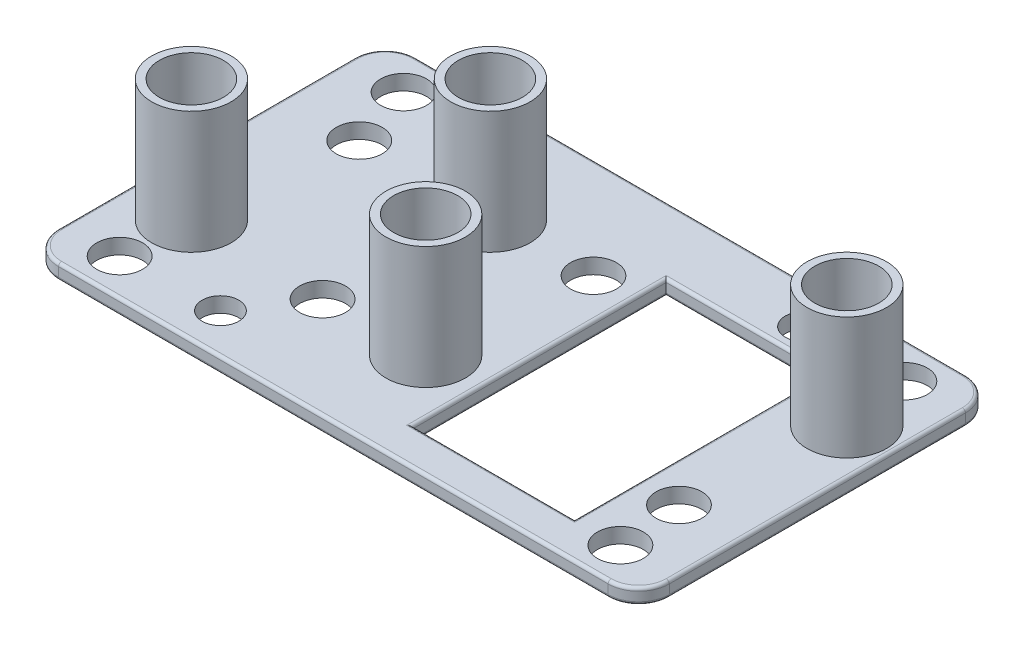
SolidWorks part; units mm, degrees
ref_plane "Front Plane" through (0, 0, 0) normal (0, 0, 1) x (1, 0, 0)
ref_plane "Top Plane" through (0, 0, 0) normal (0, 1, 0) x (1, 0, 0)
ref_plane "Right Plane" through (0, 0, 0) normal (1, 0, 0) x (0, 0, -1)
sketch "Sketch1" plane through (0, 0, 0) normal (0, 1, 0) x (1, 0, 0)
  line L1 (0, 0) -> (200, 0)
  line L2 (0, 0) -> (0, 117)
  line L3 (0, 117) -> (200, 117)
  line L4 (200, 0) -> (200, 117)
  line L5 (6.4676, 96) -> (81.4676, 96)
  line L6 (6.4676, 96) -> (6.4676, 21)
  line L7 (6.4676, 21) -> (81.4676, 21)
  line L8 (81.4676, 96) -> (81.4676, 21)
  line L9 (83.1891, 96) -> (198.1891, 96)
  line L10 (83.1891, 96) -> (83.1891, 21)
  line L11 (83.1891, 21) -> (198.1891, 21)
  line L12 (198.1891, 96) -> (198.1891, 21)
  circle A0 centre (18, 105) radius 7.5175
  circle A1 centre (18, 12) radius 7.5175
  circle A2 centre (182, 105) radius 7.5175
  circle A3 centre (182, 12) radius 7.5175
  circle A4 centre (24.4676, 84) radius 7.5175
  circle A5 centre (19.4876, 34.02) radius 6
  circle A6 centre (63.4676, 33) radius 7.5175
  circle A7 centre (68.4476, 82.98) radius 6
  circle A8 centre (101.1891, 84) radius 7.5
  circle A10 centre (180.1891, 33) radius 7.5
  circle A11 centre (185.1691, 82.98) radius 6
  circle A12 centre (96.2091, 34.02) radius 6
  circle A13 centre (96.2091, 34.02) radius 13.02
  circle A14 centre (185.1691, 82.98) radius 13.02
  circle A15 centre (68.4476, 82.98) radius 13.02
  circle A16 centre (19.4876, 34.02) radius 13.02
  circle A17 centre (47.8906, 105) radius 5.3959
  circle A18 centre (159.021, 13.6694) radius 4.7979
  circle A19 centre (50, 13.015) radius 6
  circle A20 centre (150, 103.985) radius 6
  dimension "D1" = 15.035
  dimension "D2" = 12
  dimension "D38" = 15
  dimension "D43" = 12
  dimension "D44" = 12
  dimension "D46" = 9.5959
  dimension "D48" = 15.035
  dimension "D3" = 18
  dimension "D4" = 12
  dimension "D5" = 12
  dimension "D6" = 18
  dimension "D7" = 18
  dimension "D8" = 12
  dimension "D9" = 12
  dimension "D10" = 18
  dimension "D11" = 13.02
  dimension "D12" = 13.02
  dimension "D13" = 18
  dimension "D14" = 12
  dimension "D15" = 13.02
  dimension "D16" = 13.02
  dimension "D17" = 13.02
  dimension "D18" = 13.02
  dimension "D19" = 13.02
  dimension "D20" = 13.02
  dimension "D21" = 18
  dimension "D22" = 12
  dimension "D23" = 18
  dimension "D24" = 12
  dimension "D25" = 18
  dimension "D26" = 12
  dimension "D27" = 18
  dimension "D28" = 75
  dimension "D29" = 75
  dimension "D30" = 115
  dimension "D31" = 75
  dimension "D32" = 21
  dimension "D33" = 21
  dimension "D34" = 6.4676
  dimension "D35" = 1.8109
  dimension "D36" = 200
  dimension "D37" = 117
  dimension "D39" = 50
  dimension "D40" = 50
  dimension "D41" = 13.015
  dimension "D42" = 13.015
  dimension "D45" = 13.6694
  dimension "D47" = 40.979
extrude "Boss-Extrude1" add sketch "Sketch1" along normal blind 5 contours L2 L1 L4 L3 | A0 | A4 | A5 | A16 | A7 | A6 | A8 | A2 | A3 | A1 | A12 | A10 | A14 | A13 | A15
sketch "Sketch2" plane through (0, 5, 0) normal (0, 1, 0) x (1, 0, 0)
  line L0 (200, 117) -> (200, 0)
  line L2 (200, 0) -> (0, 0)
  line L3 (200, 0) -> (0, 0)
  line L4 (0, 0) -> (0, 117)
  line L6 (0, 117) -> (200, 117)
  line L8 (200, 117) -> (200, 0)
  line L10 (200, 0) -> (0, 0)
  line L11 (200, 0) -> (0, 0)
  line L12 (0, 0) -> (0, 117)
  line L14 (0, 117) -> (200, 117)
  circle A2 centre (185.1691, 82.98) radius 13.02 construction
  circle A3 centre (96.2091, 34.02) radius 13.02 construction
  circle A6 centre (68.4476, 82.98) radius 13.02 construction
  circle A10 centre (185.1691, 82.98) radius 13.02
  circle A11 centre (96.2091, 34.02) radius 13.02
  circle A14 centre (68.4476, 82.98) radius 13.02
  circle A16 centre (19.4876, 34.02) radius 13.02 construction
  circle A17 centre (19.4876, 34.02) radius 13.02
extrude "Boss-Extrude2" add sketch "Sketch2" against normal blind 5 and the other way blind 40 contours A14 | A17 | A11 | A10
sketch "Sketch3" plane through (0, 5, 0) normal (0, 1, 0) x (1, 0, 0)
  circle A0 centre (19.4876, 34.02) radius 10.5
  circle A2 centre (96.2091, 34.02) radius 10.5
  circle A3 centre (185.1691, 82.98) radius 10.5
  circle A8 centre (68.4476, 82.98) radius 10.5
  dimension "D1" = 21
  dimension "D2" = 21
  dimension "D3" = 21
  dimension "D4" = 21
extrude "Cut-Extrude4" cut sketch "Sketch3" along normal blind 40
sketch "Sketch4" plane through (0, 0, 0) normal (0, -1, 0) x (1, 0, 0)
  circle A0 centre (19.4876, -34.02) radius 3.75
  circle A1 centre (68.4476, -82.98) radius 3.75
  circle A2 centre (96.2091, -34.02) radius 3.75
  circle A3 centre (185.1691, -82.98) radius 3.75
  dimension "D1" = 7.5
  dimension "D2" = 7.5
  dimension "D3" = 7.5
  dimension "D4" = 7.5
extrude "Cut-Extrude5" cut sketch "Sketch4" against normal blind 40
fillet "Fillet1" radius 10 4 edges at (200, 2.5, -117) (0, 2.5, -117) (0, 2.5, 0) (200, 2.5, 0)
sketch "Sketch5" plane through (0, 5, 0) normal (0, 1, 0) x (1, 0, 0)
  line L0 (200, 10) -> (200, 107) construction
  line L1 (0, 10) -> (0, 107) construction
  line L2 (10, 0) -> (190, 0) construction
  line L3 (10, 117) -> (190, 117) construction
  circle A0 centre (50, 13.02) radius 6
  circle A1 centre (150, 103.98) radius 6
  dimension "D4" = 12
  dimension "D6" = 12
  dimension "D1" = 50
  dimension "D2" = 50
  dimension "D3" = 13.02
  dimension "D5" = 13.02
extrude "Cut-Extrude6" cut sketch "Sketch5" against normal blind 10
fillet "Fillet2" radius 1 16 edges at (2.9289, 0, -2.9289) (0, 0, -58.5) (2.9289, 0, -114.0711) (100, 0, -117) (197.0711, 0, -114.0711) (200, 0, -58.5) (197.0711, 0, -2.9289) (2.9289, 5, -2.9289) (0, 5, -58.5) (2.9289, 5, -114.0711) (100, 5, -117) (197.0711, 5, -114.0711) (200, 5, -58.5) (197.0711, 5, -2.9289) (100, 0, 0) (100, 5, 0)
sketch "Sketch6" plane through (0, 5, 0) normal (0, 1, 0) x (1, 0, 0)
  line L0 (10, 117) -> (190, 117) construction
  line L1 (114, 95) -> (167, 95)
  line L2 (114, 95) -> (114, 12)
  line L3 (114, 12) -> (167, 12)
  line L4 (167, 95) -> (167, 12)
  line L5 (190, 0) -> (10, 0) construction
  line L8 (200, 107) -> (200, 10) construction
  dimension "D3" = 83
  dimension "D1" = 22
  dimension "D2" = 12
  dimension "D4" = 53
  dimension "D5" = 33
extrude "Cut-Extrude15" cut sketch "Sketch6" against normal blind 10
fillet "Fillet3" radius 1 7 edges at (167, 0, -53.5) (140.5, 5, -12) (140.5, 0, -95) (167, 5, -53.5) (140.5, 5, -95) (114, 0, -53.5) (114, 5, -53.5)
fillet "Fillet4" radius 1 1 edges at (140.5, 0, -12)
fillet "Fillet5" radius 1 1 edges at (68.4476, 5, -79.23)
fillet "Fillet6" radius 1 1 edges at (19.4876, 5, -30.27)
fillet "Fillet7" radius 1 1 edges at (96.2091, 5, -30.27)
fillet "Fillet8" radius 1 1 edges at (185.1691, 5, -79.23)
sketch "Sketch7" plane through (0, 0, 0) normal (0, -1, 0) x (1, 0, 0)
  circle A0 centre (19.4876, -34.02) radius 8
  circle A1 centre (96.2091, -34.02) radius 8
  circle A2 centre (68.4476, -82.98) radius 8
  circle A3 centre (185.1691, -82.98) radius 8
  dimension "D1" = 16
  dimension "D2" = 16
  dimension "D3" = 16
  dimension "D4" = 16
extrude "Cut-Extrude16" cut sketch "Sketch7" against normal blind 10
fillet "Fillet9" radius 1 1 edges at (185.1691, 0, -90.98)
fillet "Fillet10" radius 1 1 edges at (19.4876, 0, -42.02)
fillet "Fillet11" radius 1 1 edges at (96.2091, 0, -42.02)
fillet "Fillet12" radius 1 1 edges at (68.4476, 0, -90.98)
